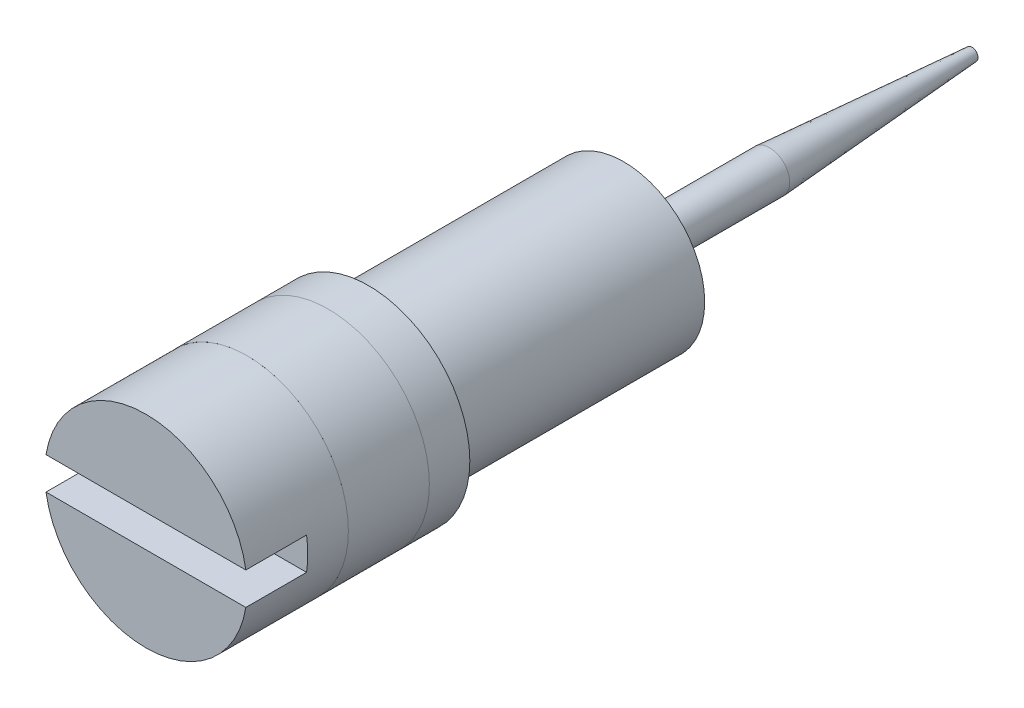
SolidWorks part; units mm, degrees
material "Stainless Steel (ferritic)"
ref_plane "Front" through (0, 0, 0) normal (0, 0, 1) x (1, 0, 0)
ref_plane "Top" through (0, 0, 0) normal (0, 1, 0) x (1, 0, 0)
ref_plane "Right" through (0, 0, 0) normal (1, 0, 0) x (0, 0, -1)
sketch "Sketch1" plane through (0, 0, 0) normal (0, 0, 1) x (1, 0, 0)
  circle A0 centre (0, 0) radius 2.5
extrude "Boss-Extrude1" add sketch "Sketch1" along normal blind 2.5
sketch "Sketch2" plane through (0, 0, 2.5) normal (0, 0, 1) x (1, 0, 0)
  line L1 (-5.7006, 0.4) -> (5.7006, 0.4)
  line L2 (-5.7006, 0.4) -> (-5.7006, -0.4)
  line L3 (-5.7006, -0.4) -> (5.7006, -0.4)
  line L4 (5.7006, 0.4) -> (5.7006, -0.4)
  line L5 (-5.7006, 0.4) -> (5.7006, -0.4) construction
  line L6 (-5.7006, -0.4) -> (5.7006, 0.4) construction
  point P0 (0, 0)
  dimension "D1" = 0.8
extrude "Cut-Extrude1" cut sketch "Sketch2" against normal blind 1.5
sketch "Sketch3" plane through (0, 0, 0) normal (0, 0, -1) x (-1, 0, 0)
  circle A0 centre (0, 0) radius 1.65
extrude "Boss-Extrude2" add sketch "Sketch3" along normal blind 2
sketch "Sketch4" plane through (0, 0, -2) normal (0, 0, -1) x (-1, 0, 0)
  circle A0 centre (0, 0) radius 2.5
extrude "Boss-Extrude3" add sketch "Sketch4" along normal blind 1
ref_plane "Plane1" through (0, 0, 0) normal (0, -1, 0) x (-1, 0, 0)
sketch "Sketch5" plane through (0, 0, 0) normal (0, -1, 0) x (-1, 0, 0)
  line L0 (0, -4.0436) -> (0, 6.0669) construction
  line L2 (-1.65, 0) -> (-2.5, 0)
  line L3 (-1.65, 0) -> (-1.65, 2)
  line L4 (-1.65, 2) -> (-2.5, 2)
  line L5 (-2.5, 0) -> (-2.5, 2)
  line L6 (-2.075, 2) -> (-2.075, 0) construction
  line L7 (-1.65, 1) -> (-2.5, 1) construction
  point P83 (-2.075, 1)
revolve "Revolve1" add sketch "Sketch5" angle 360 about L0
sketch "Sketch6" plane through (0, 0, -3) normal (0, 0, -1) x (-1, 0, 0)
  circle A0 centre (0, 0) radius 2
  dimension "D1" = 4
extrude "Boss-Extrude4" add sketch "Sketch6" along normal blind 6.3
cosmetic thread "Cosmetic Thread1" parameters "D1"=5.3, "D2"=3.22
sketch "Sketch7" plane through (0, 0, -9.3) normal (0, 0, -1) x (-1, 0, 0)
  circle A0 centre (0, 0) radius 0.5
extrude "Boss-Extrude5" add sketch "Sketch7" along normal blind 3.6
sketch "Sketch8" plane through (0, 0, -12.9) normal (0, 0, -1) x (-1, 0, 0)
  circle A0 centre (0, 0) radius 0.5
extrude "Boss-Extrude6" add sketch "Sketch8" along normal blind 5 draft 4
